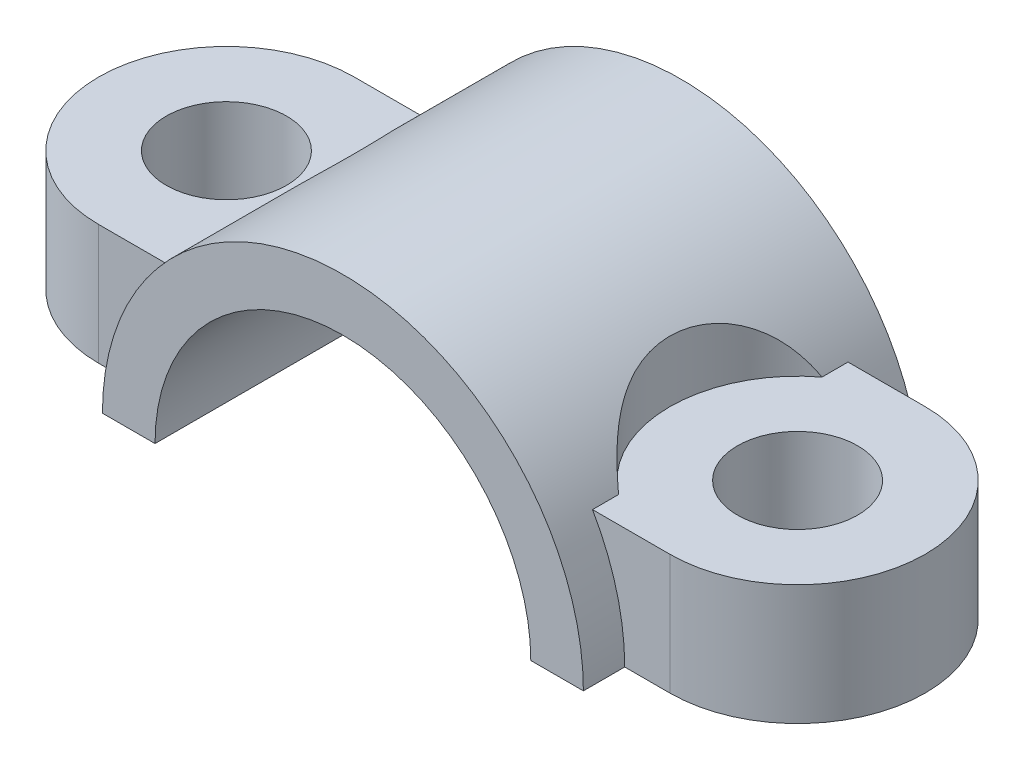
SolidWorks part; units mm, degrees
ref_plane "前视基准面" through (0, 0, 0) normal (0, 0, 1) x (1, 0, 0)
ref_plane "上视基准面" through (0, 0, 0) normal (0, 1, 0) x (1, 0, 0)
ref_plane "右视基准面" through (0, 0, 0) normal (1, 0, 0) x (0, 0, -1)
sketch "草图4" plane through (0, 0, 0) normal (0, 1, 0) x (1, 0, 0)
  line L0 (0, 12.1506) -> (0, -8.6135) construction
  circle A0 centre (-19, 0) radius 4
  circle A2 centre (-19, 0) radius 8.5
  circle A3 centre (19, 0) radius 4
  circle A4 centre (19, 0) radius 8.5
  dimension "D1" = 8
  dimension "D2" = 19
  dimension "D3" = 17
extrude "凸台-拉伸1" add sketch "草图4" along normal blind 8
sketch "草图5" plane through (0, 0, 0) normal (0, 0, 1) x (1, 0, 0)
  circle A0 centre (0, 0) radius 12.5
  dimension "D2" = 25
extrude "切除-拉伸1" cut sketch "草图5" against normal mid plane 20
sketch "草图6" plane through (0, 0, 0) normal (0, 0, 1) x (1, 0, 0)
  line L7 (-16, 0) -> (-12.5, 0)
  line L8 (12.5, 0) -> (16, 0)
  arc A3 (16, 0) -> (-16, 0) centre (0, 0) ccw
  arc A4 (12.5, 0) -> (-12.5, 0) centre (0, 0) ccw
  dimension "D1" = 32
extrude "凸台-拉伸3" add sketch "草图6" along normal mid plane 22.5
sketch "草图7" plane through (0, 8, 0) normal (0, 1, 0) x (1, 0, 0)
  circle A0 centre (-19, 0) radius 8.5
extrude "切除-拉伸2" cut sketch "草图7" along normal through all
sketch "草图8" plane through (0, 8, 0) normal (0, 1, 0) x (1, 0, 0)
  line L5 (-19, -8.5) -> (-19, -4)
  line L6 (-19, 4) -> (-19, 8.5)
  line L7 (-19, 8.5) -> (-13.4618, 8.5)
  line L8 (-13.4618, 8.5) -> (-13.4618, -8.5)
  line L9 (-13.4618, -8.5) -> (-19, -8.5)
  arc A3 (-19, -4) -> (-19, 4) centre (-19, 0) ccw
  arc A4 (-13.8564, 6.7671) -> (-13.8564, -6.7671) centre (-19, 0) ccw construction
  point P10 (-13.4618, -8.5)
extrude "凸台-拉伸4" add sketch "草图8" against normal up to surface (8 mm away) up to face at (-19.5, 0, 0)
sketch "草图9" plane through (0, 8, 0) normal (0, 1, 0) x (1, 0, 0)
  circle A0 centre (-19, 0) radius 4
extrude "切除-拉伸3" cut sketch "草图9" against normal through all
mirror "镜向1" about plane through (0, 0, 0) normal (1, 0, 0) of "切除-拉伸2", "凸台-拉伸4", "切除-拉伸3"
